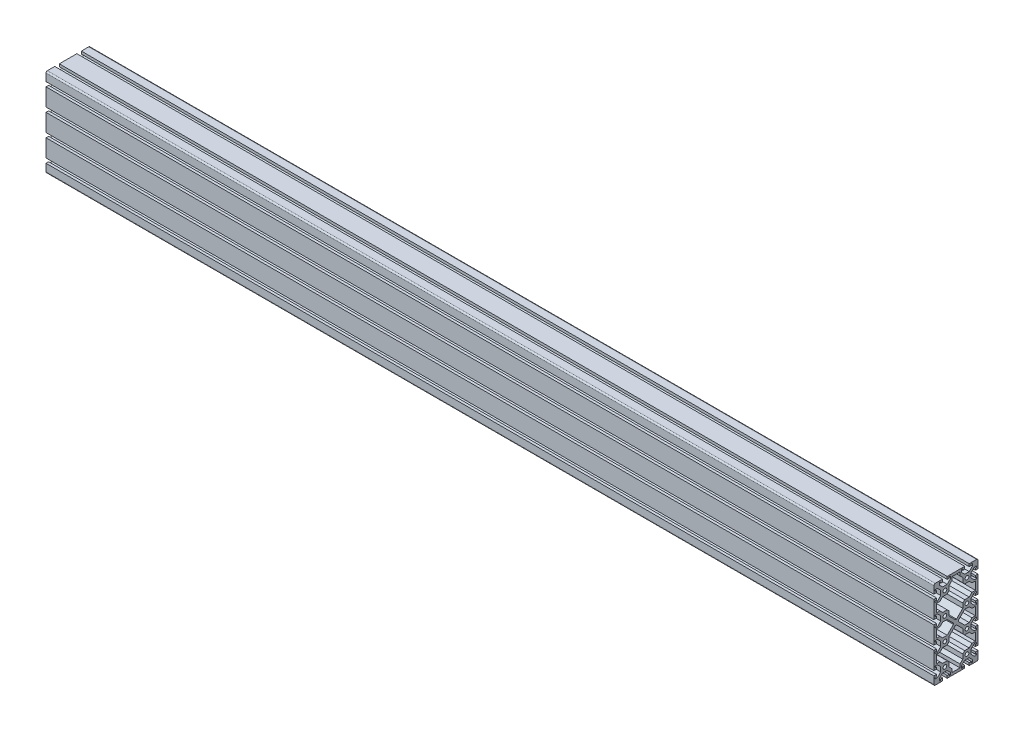
SolidWorks part; units mm, degrees
material "6063-T5"
ref_plane "Front Plane" through (0, 0, 0) normal (0, 0, 1) x (1, 0, 0)
ref_plane "Top Plane" through (0, 0, 0) normal (0, 1, 0) x (1, 0, 0)
ref_plane "Right Plane" through (0, 0, 0) normal (1, 0, 0) x (0, 0, -1)
sketch "Sketch1" plane through (0, 0, 0) normal (0, 1, 0) x (1, 0, 0)
  line L0 (-805, 0) -> (805, 0)
  dimension "D1" = 1610
other "80 series TS80-160M(1)"
ref_plane "Plane1" through (-805, 0, 0) normal (1, 0, 0) x (0, 0, -1)
sketch "Sketch22" plane through (-805, 0, 0) normal (1, 0, 0) x (0, 0, -1)
  line L0 (20, -20) -> (0, 0) construction
  line L1 (20, -20) -> (27.6, -20) construction
  line L2 (27.6, -15.9) -> (27.6, -24.1)
  line L3 (27.6, -24.1) -> (33.6, -30.1)
  line L4 (33.6, -30.1) -> (37.65, -30.1)
  line L5 (37.65, -30.1) -> (37.65, -27.6)
  line L6 (37.65, -27.6) -> (35.3, -27.6)
  line L7 (35.3, -27.6) -> (35.3, -24.1)
  line L8 (35.3, -24.1) -> (40, -24.1)
  line L9 (20, -20) -> (20, -27.6) construction
  line L10 (20, -27.6) -> (24.1, -27.6)
  line L11 (24.1, -27.6) -> (29.1, -32.6)
  line L12 (29.1, -32.6) -> (35.3, -32.6)
  line L13 (40, -40) -> (20, -20) construction
  line L14 (35.3, -32.6) -> (35.3, -47.4)
  line L15 (35.3, -40) -> (40, -40) construction
  line L16 (40, -24.1) -> (40, -55.9)
  line L17 (20, -12.4) -> (24.1, -12.4)
  line L18 (24.1, -12.4) -> (29.1, -7.4)
  line L19 (29.1, -7.4) -> (35.3, -7.4)
  line L20 (35.3, -7.4) -> (35.3, 7.4)
  line L21 (40, 0) -> (20, -20) construction
  line L22 (35.3, 0) -> (40, 0) construction
  line L23 (40, -15.9) -> (40, 15.9)
  line L24 (35.3, -15.9) -> (40, -15.9)
  line L25 (35.3, -12.4) -> (35.3, -15.9)
  line L26 (37.65, -12.4) -> (35.3, -12.4)
  line L27 (37.65, -9.9) -> (37.65, -12.4)
  line L28 (33.6, -9.9) -> (37.65, -9.9)
  line L29 (27.6, -15.9) -> (33.6, -9.9)
  line L30 (40, -40) -> (20, -60) construction
  line L31 (40, -80) -> (20, -60) construction
  line L32 (7.4, -69.1) -> (7.4, -75.3)
  line L33 (20, -52.4) -> (24.1, -52.4)
  line L34 (12.4, -64.1) -> (7.4, -69.1)
  line L35 (27.6, -64.1) -> (33.6, -70.1)
  line L36 (33.6, -70.1) -> (37.65, -70.1)
  line L37 (37.65, -70.1) -> (37.65, -67.6)
  line L38 (37.65, -67.6) -> (35.3, -67.6)
  line L39 (35.3, -67.6) -> (35.3, -64.1)
  line L40 (35.3, -64.1) -> (40, -64.1)
  line L41 (40, -64.1) -> (40, -77.5)
  line L42 (12.4, -60) -> (12.4, -64.1)
  line L43 (15.9, -75.3) -> (15.9, -80)
  line L44 (12.4, -75.3) -> (15.9, -75.3)
  line L45 (29.1, -47.4) -> (35.3, -47.4)
  line L46 (24.1, -52.4) -> (29.1, -47.4)
  line L47 (35.3, -55.9) -> (40, -55.9)
  line L48 (35.3, -52.4) -> (35.3, -55.9)
  line L49 (37.65, -52.4) -> (35.3, -52.4)
  line L50 (37.65, -49.9) -> (37.65, -52.4)
  line L51 (33.6, -49.9) -> (37.65, -49.9)
  line L52 (27.6, -55.9) -> (33.6, -49.9)
  line L53 (27.6, -64.1) -> (27.6, -55.9)
  line L54 (12.4, -77.65) -> (12.4, -75.3)
  line L55 (9.9, -77.65) -> (12.4, -77.65)
  line L56 (9.9, -73.6) -> (9.9, -77.65)
  line L57 (15.9, -67.6) -> (9.9, -73.6)
  line L58 (24.1, -67.6) -> (15.9, -67.6)
  line L59 (24.1, -67.6) -> (30.1, -73.6)
  line L60 (30.1, -73.6) -> (30.1, -77.65)
  line L61 (27.6, -77.65) -> (27.6, -75.3)
  line L62 (30.1, -77.65) -> (27.6, -77.65)
  line L63 (27.6, -75.3) -> (24.1, -75.3)
  line L64 (24.1, -75.3) -> (24.1, -80)
  line L65 (24.1, -80) -> (37.5, -80)
  line L66 (7.4, -75.3) -> (-7.4, -75.3)
  line L67 (0, -75.3) -> (0, -80) construction
  line L68 (-15.9, -80) -> (15.9, -80)
  line L69 (20, -12.4) -> (15.9, -12.4)
  line L70 (15.9, -12.4) -> (4.5, -1)
  line L71 (4.5, -1) -> (4.5, 1)
  line L72 (-1, -4.5) -> (1, -4.5)
  line L73 (1, -4.5) -> (12.4, -15.9)
  line L74 (12.4, -15.9) -> (12.4, -24.1)
  line L75 (12.4, -24.1) -> (15.9, -27.6)
  line L76 (15.9, -27.6) -> (20, -27.6)
  line L77 (0, -55) -> (0, 55) construction
  line L78 (44, 0) -> (-44, 0) construction
  line L79 (20, -52.4) -> (15.9, -52.4)
  line L80 (15.9, -52.4) -> (12.4, -55.9)
  line L81 (12.4, -55.9) -> (12.4, -60)
  line L82 (0, 75.3) -> (0, 80) construction
  line L83 (40, 80) -> (20, 60) construction
  line L84 (40, 40) -> (20, 60) construction
  line L85 (40, 0) -> (20, 20) construction
  line L86 (35.3, 40) -> (40, 40) construction
  line L87 (40, 40) -> (20, 20) construction
  line L88 (20, 20) -> (20, 27.6) construction
  line L89 (20, 20) -> (27.6, 20) construction
  line L90 (20, 20) -> (0, 0) construction
  line L91 (12.4, 55.9) -> (12.4, 60)
  line L92 (15.9, 52.4) -> (12.4, 55.9)
  line L93 (20, 52.4) -> (15.9, 52.4)
  line L94 (15.9, 27.6) -> (20, 27.6)
  line L95 (12.4, 24.1) -> (15.9, 27.6)
  line L96 (12.4, 15.9) -> (12.4, 24.1)
  line L97 (1, 4.5) -> (12.4, 15.9)
  line L98 (-1, 4.5) -> (1, 4.5)
  line L99 (15.9, 12.4) -> (4.5, 1)
  line L100 (20, 12.4) -> (15.9, 12.4)
  line L101 (-15.9, 80) -> (15.9, 80)
  line L102 (7.4, 75.3) -> (-7.4, 75.3)
  line L103 (24.1, 80) -> (37.5, 80)
  line L104 (24.1, 75.3) -> (24.1, 80)
  line L105 (27.6, 75.3) -> (24.1, 75.3)
  line L106 (30.1, 77.65) -> (27.6, 77.65)
  line L107 (27.6, 77.65) -> (27.6, 75.3)
  line L108 (30.1, 73.6) -> (30.1, 77.65)
  line L109 (24.1, 67.6) -> (30.1, 73.6)
  line L110 (24.1, 67.6) -> (15.9, 67.6)
  line L111 (15.9, 67.6) -> (9.9, 73.6)
  line L112 (9.9, 73.6) -> (9.9, 77.65)
  line L113 (9.9, 77.65) -> (12.4, 77.65)
  line L114 (12.4, 77.65) -> (12.4, 75.3)
  line L115 (27.6, 64.1) -> (27.6, 55.9)
  line L116 (27.6, 55.9) -> (33.6, 49.9)
  line L117 (33.6, 49.9) -> (37.65, 49.9)
  line L118 (37.65, 49.9) -> (37.65, 52.4)
  line L119 (37.65, 52.4) -> (35.3, 52.4)
  line L120 (35.3, 52.4) -> (35.3, 55.9)
  line L121 (35.3, 55.9) -> (40, 55.9)
  line L122 (24.1, 52.4) -> (29.1, 47.4)
  line L123 (29.1, 47.4) -> (35.3, 47.4)
  line L124 (12.4, 75.3) -> (15.9, 75.3)
  line L125 (15.9, 75.3) -> (15.9, 80)
  line L126 (12.4, 60) -> (12.4, 64.1)
  line L127 (40, 64.1) -> (40, 77.5)
  line L128 (35.3, 64.1) -> (40, 64.1)
  line L129 (35.3, 67.6) -> (35.3, 64.1)
  line L130 (37.65, 67.6) -> (35.3, 67.6)
  line L131 (37.65, 70.1) -> (37.65, 67.6)
  line L132 (33.6, 70.1) -> (37.65, 70.1)
  line L133 (27.6, 64.1) -> (33.6, 70.1)
  line L134 (12.4, 64.1) -> (7.4, 69.1)
  line L135 (20, 52.4) -> (24.1, 52.4)
  line L136 (7.4, 69.1) -> (7.4, 75.3)
  line L137 (27.6, 15.9) -> (33.6, 9.9)
  line L138 (33.6, 9.9) -> (37.65, 9.9)
  line L139 (37.65, 9.9) -> (37.65, 12.4)
  line L140 (37.65, 12.4) -> (35.3, 12.4)
  line L141 (35.3, 12.4) -> (35.3, 15.9)
  line L142 (35.3, 15.9) -> (40, 15.9)
  line L143 (29.1, 7.4) -> (35.3, 7.4)
  line L144 (24.1, 12.4) -> (29.1, 7.4)
  line L145 (20, 12.4) -> (24.1, 12.4)
  line L146 (40, 24.1) -> (40, 55.9)
  line L147 (35.3, 32.6) -> (35.3, 47.4)
  line L148 (29.1, 32.6) -> (35.3, 32.6)
  line L149 (24.1, 27.6) -> (29.1, 32.6)
  line L150 (20, 27.6) -> (24.1, 27.6)
  line L151 (35.3, 24.1) -> (40, 24.1)
  line L152 (35.3, 27.6) -> (35.3, 24.1)
  line L153 (37.65, 27.6) -> (35.3, 27.6)
  line L154 (37.65, 30.1) -> (37.65, 27.6)
  line L155 (33.6, 30.1) -> (37.65, 30.1)
  line L156 (27.6, 24.1) -> (33.6, 30.1)
  line L157 (27.6, 15.9) -> (27.6, 24.1)
  line L158 (-20, 20) -> (0, 0) construction
  line L159 (-20, 20) -> (-27.6, 20) construction
  line L160 (-20, 20) -> (-20, 27.6) construction
  line L161 (-40, 40) -> (-20, 20) construction
  line L162 (-35.3, 40) -> (-40, 40) construction
  line L163 (-40, 0) -> (-20, 20) construction
  line L164 (-40, 40) -> (-20, 60) construction
  line L165 (-40, 80) -> (-20, 60) construction
  line L166 (-40, -80) -> (-20, -60) construction
  line L167 (-40, -40) -> (-20, -60) construction
  line L168 (-35.3, 0) -> (-40, 0) construction
  line L169 (-40, 0) -> (-20, -20) construction
  line L170 (-35.3, -40) -> (-40, -40) construction
  line L171 (-40, -40) -> (-20, -20) construction
  line L172 (-20, -20) -> (-20, -27.6) construction
  line L173 (-20, -20) -> (-27.6, -20) construction
  line L174 (-20, -20) -> (0, 0) construction
  line L175 (-27.6, 15.9) -> (-27.6, 24.1)
  line L176 (-27.6, 24.1) -> (-33.6, 30.1)
  line L177 (-33.6, 30.1) -> (-37.65, 30.1)
  line L178 (-37.65, 30.1) -> (-37.65, 27.6)
  line L179 (-37.65, 27.6) -> (-35.3, 27.6)
  line L180 (-35.3, 27.6) -> (-35.3, 24.1)
  line L181 (-35.3, 24.1) -> (-40, 24.1)
  line L182 (-20, 27.6) -> (-24.1, 27.6)
  line L183 (-24.1, 27.6) -> (-29.1, 32.6)
  line L184 (-29.1, 32.6) -> (-35.3, 32.6)
  line L185 (-35.3, 32.6) -> (-35.3, 47.4)
  line L186 (-40, 24.1) -> (-40, 55.9)
  line L187 (-20, 12.4) -> (-24.1, 12.4)
  line L188 (-24.1, 12.4) -> (-29.1, 7.4)
  line L189 (-29.1, 7.4) -> (-35.3, 7.4)
  line L190 (-35.3, 15.9) -> (-40, 15.9)
  line L191 (-35.3, 12.4) -> (-35.3, 15.9)
  line L192 (-37.65, 12.4) -> (-35.3, 12.4)
  line L193 (-37.65, 9.9) -> (-37.65, 12.4)
  line L194 (-33.6, 9.9) -> (-37.65, 9.9)
  line L195 (-27.6, 15.9) -> (-33.6, 9.9)
  line L196 (-7.4, 69.1) -> (-7.4, 75.3)
  line L197 (-20, 52.4) -> (-24.1, 52.4)
  line L198 (-12.4, 64.1) -> (-7.4, 69.1)
  line L199 (-27.6, 64.1) -> (-33.6, 70.1)
  line L200 (-33.6, 70.1) -> (-37.65, 70.1)
  line L201 (-37.65, 70.1) -> (-37.65, 67.6)
  line L202 (-37.65, 67.6) -> (-35.3, 67.6)
  line L203 (-35.3, 67.6) -> (-35.3, 64.1)
  line L204 (-35.3, 64.1) -> (-40, 64.1)
  line L205 (-40, 64.1) -> (-40, 77.5)
  line L206 (-12.4, 60) -> (-12.4, 64.1)
  line L207 (-15.9, 75.3) -> (-15.9, 80)
  line L208 (-12.4, 75.3) -> (-15.9, 75.3)
  line L209 (-29.1, 47.4) -> (-35.3, 47.4)
  line L210 (-24.1, 52.4) -> (-29.1, 47.4)
  line L211 (-35.3, 55.9) -> (-40, 55.9)
  line L212 (-35.3, 52.4) -> (-35.3, 55.9)
  line L213 (-37.65, 52.4) -> (-35.3, 52.4)
  line L214 (-37.65, 49.9) -> (-37.65, 52.4)
  line L215 (-33.6, 49.9) -> (-37.65, 49.9)
  line L216 (-27.6, 55.9) -> (-33.6, 49.9)
  line L217 (-27.6, 64.1) -> (-27.6, 55.9)
  line L218 (-12.4, 77.65) -> (-12.4, 75.3)
  line L219 (-9.9, 77.65) -> (-12.4, 77.65)
  line L220 (-9.9, 73.6) -> (-9.9, 77.65)
  line L221 (-15.9, 67.6) -> (-9.9, 73.6)
  line L222 (-24.1, 67.6) -> (-15.9, 67.6)
  line L223 (-24.1, 67.6) -> (-30.1, 73.6)
  line L224 (-30.1, 73.6) -> (-30.1, 77.65)
  line L225 (-27.6, 77.65) -> (-27.6, 75.3)
  line L226 (-30.1, 77.65) -> (-27.6, 77.65)
  line L227 (-27.6, 75.3) -> (-24.1, 75.3)
  line L228 (-24.1, 75.3) -> (-24.1, 80)
  line L229 (-24.1, 80) -> (-37.5, 80)
  line L230 (-20, 12.4) -> (-15.9, 12.4)
  line L231 (-15.9, 12.4) -> (-4.5, 1)
  line L232 (-1, 4.5) -> (-12.4, 15.9)
  line L233 (-12.4, 15.9) -> (-12.4, 24.1)
  line L234 (-12.4, 24.1) -> (-15.9, 27.6)
  line L235 (-15.9, 27.6) -> (-20, 27.6)
  line L236 (-20, 52.4) -> (-15.9, 52.4)
  line L237 (-15.9, 52.4) -> (-12.4, 55.9)
  line L238 (-12.4, 55.9) -> (-12.4, 60)
  line L239 (-12.4, -55.9) -> (-12.4, -60)
  line L240 (-15.9, -52.4) -> (-12.4, -55.9)
  line L241 (-20, -52.4) -> (-15.9, -52.4)
  line L242 (-15.9, -27.6) -> (-20, -27.6)
  line L243 (-12.4, -24.1) -> (-15.9, -27.6)
  line L244 (-12.4, -15.9) -> (-12.4, -24.1)
  line L245 (-1, -4.5) -> (-12.4, -15.9)
  line L246 (-4.5, -1) -> (-4.5, 1)
  line L247 (-15.9, -12.4) -> (-4.5, -1)
  line L248 (-20, -12.4) -> (-15.9, -12.4)
  line L249 (-24.1, -80) -> (-37.5, -80)
  line L250 (-24.1, -75.3) -> (-24.1, -80)
  line L251 (-27.6, -75.3) -> (-24.1, -75.3)
  line L252 (-30.1, -77.65) -> (-27.6, -77.65)
  line L253 (-27.6, -77.65) -> (-27.6, -75.3)
  line L254 (-30.1, -73.6) -> (-30.1, -77.65)
  line L255 (-24.1, -67.6) -> (-30.1, -73.6)
  line L256 (-24.1, -67.6) -> (-15.9, -67.6)
  line L257 (-15.9, -67.6) -> (-9.9, -73.6)
  line L258 (-9.9, -73.6) -> (-9.9, -77.65)
  line L259 (-9.9, -77.65) -> (-12.4, -77.65)
  line L260 (-12.4, -77.65) -> (-12.4, -75.3)
  line L261 (-27.6, -64.1) -> (-27.6, -55.9)
  line L262 (-27.6, -55.9) -> (-33.6, -49.9)
  line L263 (-33.6, -49.9) -> (-37.65, -49.9)
  line L264 (-37.65, -49.9) -> (-37.65, -52.4)
  line L265 (-37.65, -52.4) -> (-35.3, -52.4)
  line L266 (-35.3, -52.4) -> (-35.3, -55.9)
  line L267 (-35.3, -55.9) -> (-40, -55.9)
  line L268 (-24.1, -52.4) -> (-29.1, -47.4)
  line L269 (-29.1, -47.4) -> (-35.3, -47.4)
  line L270 (-12.4, -75.3) -> (-15.9, -75.3)
  line L271 (-15.9, -75.3) -> (-15.9, -80)
  line L272 (-12.4, -60) -> (-12.4, -64.1)
  line L273 (-40, -64.1) -> (-40, -77.5)
  line L274 (-35.3, -64.1) -> (-40, -64.1)
  line L275 (-35.3, -67.6) -> (-35.3, -64.1)
  line L276 (-37.65, -67.6) -> (-35.3, -67.6)
  line L277 (-37.65, -70.1) -> (-37.65, -67.6)
  line L278 (-33.6, -70.1) -> (-37.65, -70.1)
  line L279 (-27.6, -64.1) -> (-33.6, -70.1)
  line L280 (-12.4, -64.1) -> (-7.4, -69.1)
  line L281 (-20, -52.4) -> (-24.1, -52.4)
  line L282 (-7.4, -69.1) -> (-7.4, -75.3)
  line L283 (-27.6, -15.9) -> (-33.6, -9.9)
  line L284 (-33.6, -9.9) -> (-37.65, -9.9)
  line L285 (-37.65, -9.9) -> (-37.65, -12.4)
  line L286 (-37.65, -12.4) -> (-35.3, -12.4)
  line L287 (-35.3, -12.4) -> (-35.3, -15.9)
  line L288 (-35.3, -15.9) -> (-40, -15.9)
  line L289 (-40, -15.9) -> (-40, 15.9)
  line L290 (-35.3, -7.4) -> (-35.3, 7.4)
  line L291 (-29.1, -7.4) -> (-35.3, -7.4)
  line L292 (-24.1, -12.4) -> (-29.1, -7.4)
  line L293 (-20, -12.4) -> (-24.1, -12.4)
  line L294 (-40, -24.1) -> (-40, -55.9)
  line L295 (-35.3, -32.6) -> (-35.3, -47.4)
  line L296 (-29.1, -32.6) -> (-35.3, -32.6)
  line L297 (-24.1, -27.6) -> (-29.1, -32.6)
  line L298 (-20, -27.6) -> (-24.1, -27.6)
  line L299 (-35.3, -24.1) -> (-40, -24.1)
  line L300 (-35.3, -27.6) -> (-35.3, -24.1)
  line L301 (-37.65, -27.6) -> (-35.3, -27.6)
  line L302 (-37.65, -30.1) -> (-37.65, -27.6)
  line L303 (-33.6, -30.1) -> (-37.65, -30.1)
  line L304 (-27.6, -24.1) -> (-33.6, -30.1)
  line L305 (-27.6, -15.9) -> (-27.6, -24.1)
  circle A0 centre (20, -60) radius 3.35
  circle A1 centre (20, -20) radius 3.35
  arc A2 (40, -77.5) -> (37.5, -80) centre (37.5, -77.5) cw
  arc A3 (40, 77.5) -> (37.5, 80) centre (37.5, 77.5) ccw
  circle A4 centre (20, 20) radius 3.35
  circle A5 centre (20, 60) radius 3.35
  circle A6 centre (-20, 60) radius 3.35
  circle A7 centre (-20, 20) radius 3.35
  arc A8 (-40, 77.5) -> (-37.5, 80) centre (-37.5, 77.5) cw
  arc A9 (-40, -77.5) -> (-37.5, -80) centre (-37.5, -77.5) ccw
  circle A10 centre (-20, -20) radius 3.35
  circle A11 centre (-20, -60) radius 3.35
  point P16 (37.65, -24.1)
  point P82 (40, -60)
  point P86 (0, 0)
  point P87 (40, 0)
  point P88 (40, -40)
  point P89 (40, -80)
  point P90 (0, -80)
  point P91 (20, -60)
  point P96 (20, -20)
  point P97 (40, -20)
  point P98 (20, -80)
  point P123 (4.5, 0)
  point P179 (20, 20)
  point P180 (40, 40)
  point P181 (20, 80)
  point P182 (40, 20)
  point P183 (20, 20)
  point P184 (20, 60)
  point P185 (0, 80)
  point P186 (40, 80)
  point P187 (40, 40)
  point P188 (40, 60)
  point P270 (40, -40)
  point P274 (20, -20)
  point P278 (0, 4.5)
  point P291 (0, -4.5)
  point P348 (-20, -20)
  point P349 (-40, -40)
  point P350 (-40, 60)
  point P351 (-40, 40)
  point P352 (-40, 80)
  point P353 (-20, 60)
  point P354 (-20, 20)
  point P355 (-40, 20)
  point P356 (-20, 80)
  point P357 (-40, 40)
  point P358 (-20, 20)
  point P359 (-4.5, 0)
  point P360 (-20, -80)
  point P361 (-40, -20)
  point P362 (-20, -20)
  point P363 (-20, -60)
  point P364 (-40, -80)
  point P365 (-40, -40)
  point P366 (-40, 0)
  point P367 (-40, -60)
  point P368 (0, 0)
  dimension "D1" = 4.1
  dimension "D2" = 10.1
  dimension "D4" = 2.5
  dimension "D9" = 20
  dimension "D3" = 4.7
  dimension "D5" = 12.4
  dimension "D10" = 2.5
  dimension "D6" = 3.35
  dimension "D8" = 20
  dimension "D7" = 2.5
  dimension "D11" = 1
hole_wizard "M8x1.25 Tapped Hole1" positions "Sketch23" profile "Sketch24" tap size "M8x1.25" standard "ANSI Metric"
sketch "Sketch23" plane through (-805, 0, 0) normal (-1, 0, 0) x (0, 0, 1)
  point P0 (-20, 60)
  point P3 (20, 60)
  point P6 (-20, -60)
  point P9 (20, -60)
sketch "Sketch24" plane through (-805, 60, -20) normal (0, 1, 0) x (0, 0, 1)
  line L0 (0, 0) -> (0, 32.0429)
  line L1 (0, 32.0429) -> (3.4, 30)
  line L2 (3.4, 30) -> (3.4, 0)
  line L5 (3.4, 0) -> (0, 0)
  line L10 (0, 32.0429) -> (-3.4, 30) construction
  line L11 (0, -6.35) -> (0, 107.95) construction
  dimension "Tap Drill Dia." = 6.8
  dimension "Tap Drill Depth" = 30
  dimension "Drill Angle" = 118
cosmetic thread "Hole Thread1" parameters "D1"=25, "D2"=8
cosmetic thread "Hole Thread2" parameters "D1"=25, "D2"=8
cosmetic thread "Hole Thread3" parameters "D1"=25, "D2"=8
cosmetic thread "Hole Thread4" parameters "D1"=25, "D2"=8
hole_wizard "M8x1.25 Tapped Hole2" positions "Sketch25" profile "Sketch26" tap size "M8x1.25" standard "ANSI Metric"
sketch "Sketch25" plane through (805, 0, 0) normal (1, 0, 0) x (0, 0, -1)
  point P0 (-20, 60)
  point P3 (20, 60)
  point P6 (20, -60)
  point P9 (-20, -60)
sketch "Sketch26" plane through (805, 60, 20) normal (0, 1, 0) x (0, 0, -1)
  line L0 (0, 0) -> (0, 32.0429)
  line L1 (0, 32.0429) -> (3.4, 30)
  line L2 (3.4, 30) -> (3.4, 0)
  line L5 (3.4, 0) -> (0, 0)
  line L10 (0, 32.0429) -> (-3.4, 30) construction
  line L11 (0, -6.35) -> (0, 107.95) construction
  dimension "Tap Drill Dia." = 6.8
  dimension "Tap Drill Depth" = 30
  dimension "Drill Angle" = 118
cosmetic thread "Hole Thread5" parameters "D1"=25, "D2"=8
cosmetic thread "Hole Thread6" parameters "D1"=25, "D2"=8
cosmetic thread "Hole Thread7" parameters "D1"=25, "D2"=8
cosmetic thread "Hole Thread8" parameters "D1"=25, "D2"=8
